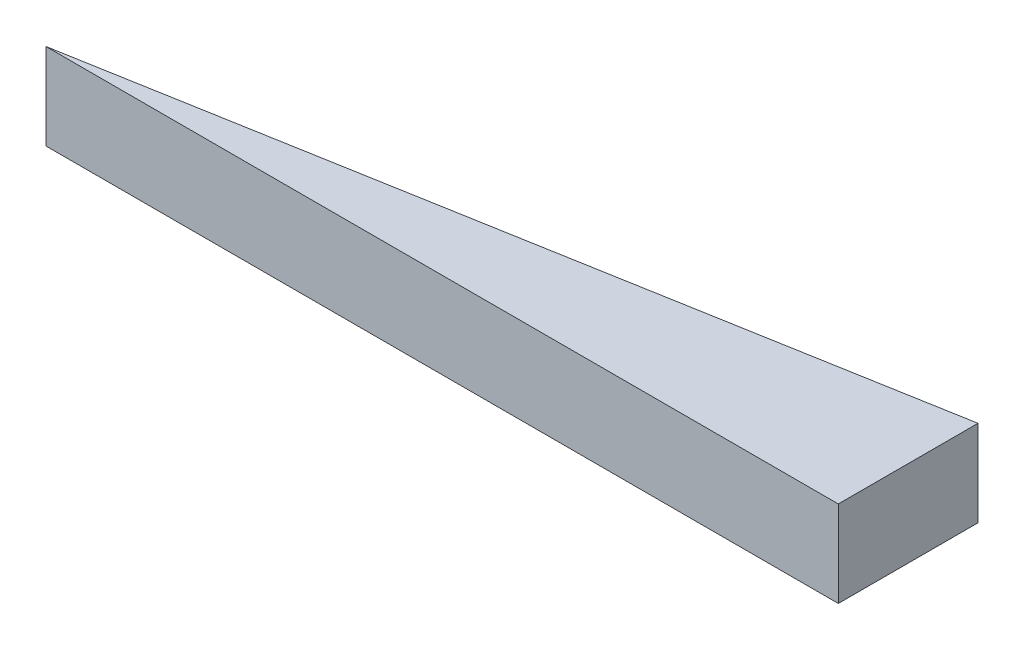
SolidWorks part; units mm, degrees
material "Pine"
ref_plane "Front Plane" through (0, 0, 0) normal (0, 0, 1) x (1, 0, 0)
ref_plane "Top Plane" through (0, 0, 0) normal (0, 1, 0) x (1, 0, 0)
ref_plane "Right Plane" through (0, 0, 0) normal (1, 0, 0) x (0, 0, -1)
sketch "Sketch1" plane through (0, 0, 0) normal (0, 1, 0) x (1, 0, 0)
  line L0 (3.641, 0) -> (178.7398, 0)
  line L1 (3.641, 0) -> (178.7398, 30.8746)
  line L2 (178.7398, 30.8746) -> (178.7398, 0)
  dimension "D1" = 177.8
  dimension "D2" = 10
  dimension "D3" = 175.0988
extrude "Boss-Extrude1" add sketch "Sketch1" along normal blind 19.05
